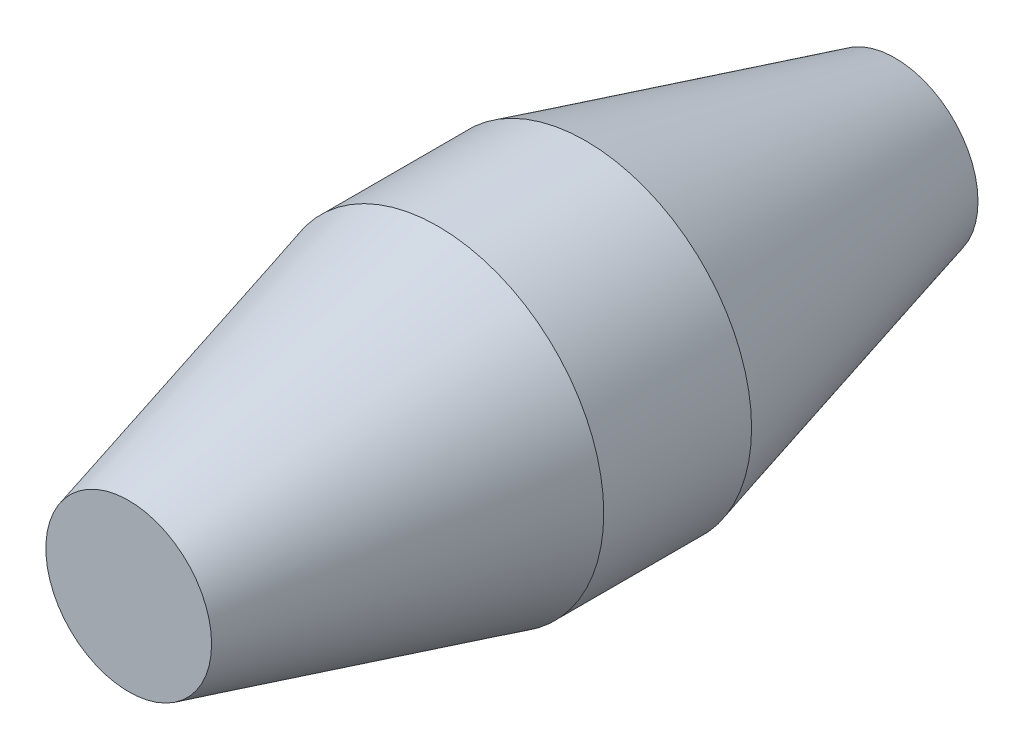
SolidWorks part; units mm, degrees
ref_plane "Front Plane" through (0, 0, 0) normal (0, 0, 1) x (1, 0, 0)
ref_plane "Top Plane" through (0, 0, 0) normal (0, 1, 0) x (1, 0, 0)
ref_plane "Right Plane" through (0, 0, 0) normal (1, 0, 0) x (0, 0, -1)
sketch "Sketch1" plane through (0, 0, 0) normal (0, 0, 1) x (1, 0, 0)
  circle A0 centre (0, 0) radius 12.7
extrude "Boss-Extrude1" add sketch "Sketch1" against normal blind 58.7248
ref_plane "Plane2" through (0, 0, -29.3624) normal (0, 0, -1) x (-1, 0, 0)
chamfer "Chamfer3" distance 6.35 angle 75 1 edges at (12.7, 0, -58.7248)
chamfer "Chamfer4" distance 6.35 angle 75 1 edges at (12.7, 0, 0)
